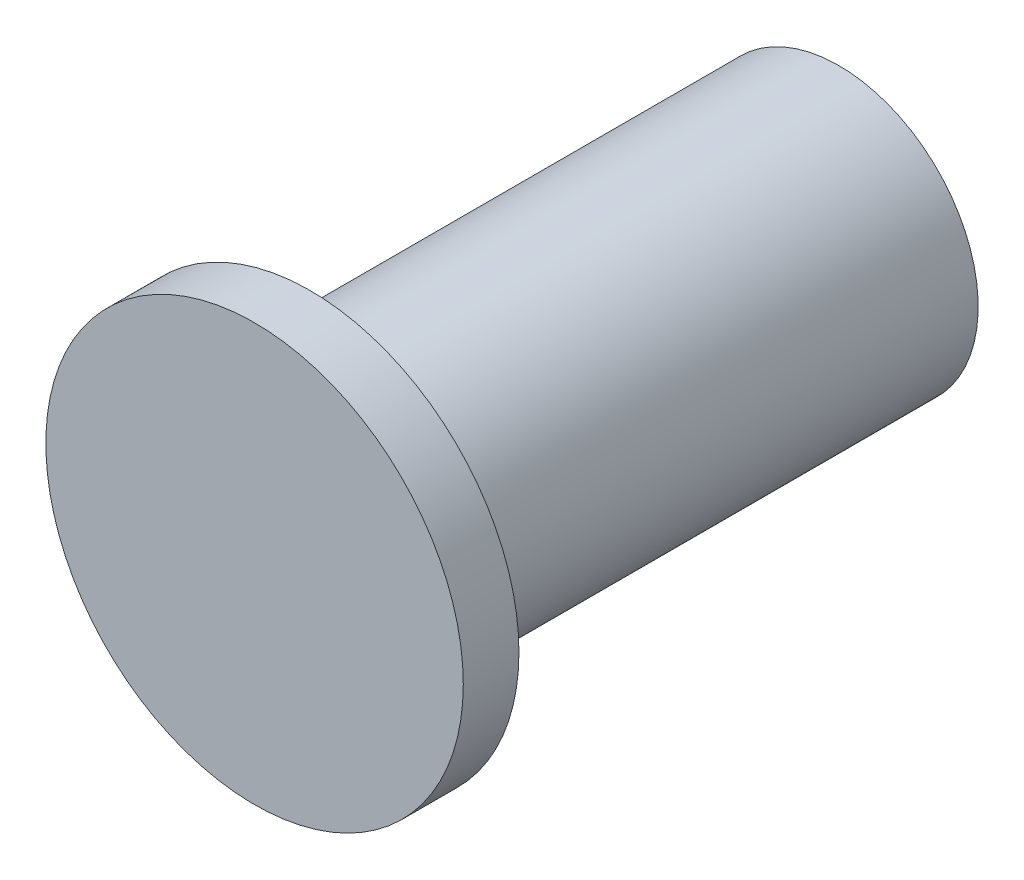
SolidWorks part; units mm, degrees
ref_plane "Plan de face" through (0, 0, 0) normal (0, 0, 1) x (1, 0, 0)
ref_plane "Plan de dessus" through (0, 0, 0) normal (0, 1, 0) x (1, 0, 0)
ref_plane "Plan de droite" through (0, 0, 0) normal (1, 0, 0) x (0, 0, -1)
sketch "Esquisse1" plane through (0, 0, 0) normal (0, 0, 1) x (1, 0, 0)
  line L5 (-15.3756, 14.4315) -> (-5.3756, 4.4315) construction
  line L6 (-15.3756, 4.4315) -> (-5.3756, 14.4315) construction
  circle A0 centre (-10.3756, 9.4315) radius 5
  dimension "D1" = 10
extrude "Boss.-Extru.1" add sketch "Esquisse1" along normal blind 21
sketch "Esquisse2" plane through (0, 0, 21) normal (0, 0, 1) x (1, 0, 0)
  circle A0 centre (-10.3756, 9.4315) radius 7.5
  dimension "D1" = 15
extrude "Boss.-Extru.2" add sketch "Esquisse2" against normal blind 2
ref_plane "Plan1" through (0, 9.5, 0) normal (0, 1, 0) x (1, 0, 0)
ref_plane "Plan2" through (-10.25, 0, 0) normal (1, 0, 0) x (0, 0, -1)
